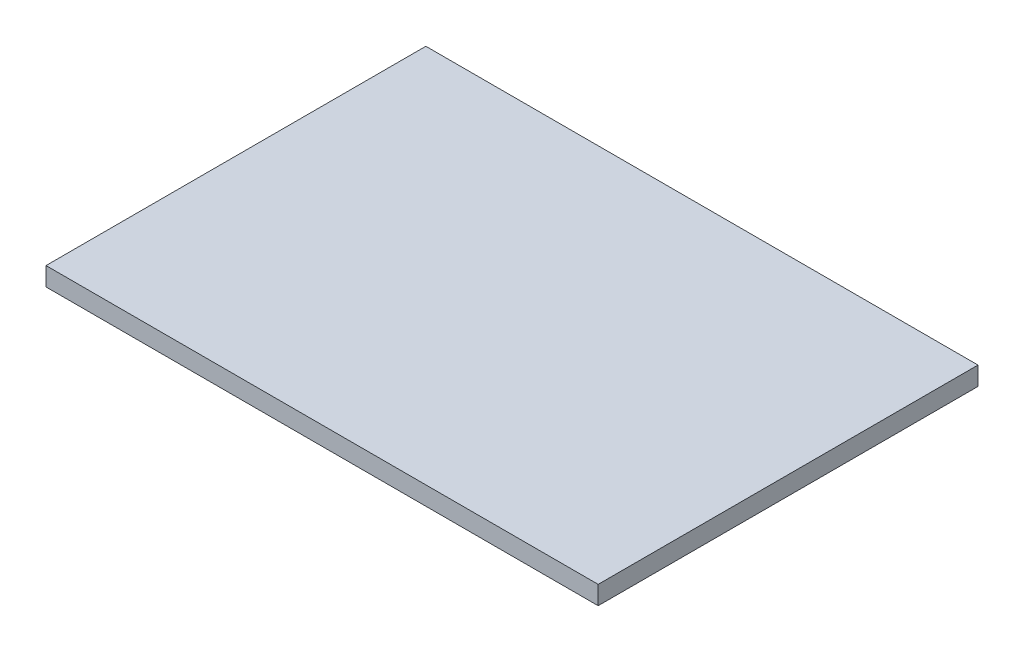
SolidWorks part; units mm, degrees
material "Керамика фарфор"
ref_plane "Спереди" through (0, 0, 0) normal (0, 0, 1) x (1, 0, 0)
ref_plane "Сверху" through (0, 0, 0) normal (0, 1, 0) x (1, 0, 0)
ref_plane "Справа" through (0, 0, 0) normal (1, 0, 0) x (0, 0, -1)
sketch "Эскиз1" plane through (0, 0, 0) normal (0, 1, 0) x (1, 0, 0)
  line L1 (-298, 205) -> (298, 205)
  line L2 (-298, 205) -> (-298, -205)
  line L3 (-298, -205) -> (298, -205)
  line L4 (298, 205) -> (298, -205)
  line L5 (-298, 205) -> (298, -205) construction
  line L6 (-298, -205) -> (298, 205) construction
  point P0 (0, 0)
  dimension "D1" = 596
  dimension "D2" = 410
extrude "База" add sketch "Эскиз1" along normal blind 20
